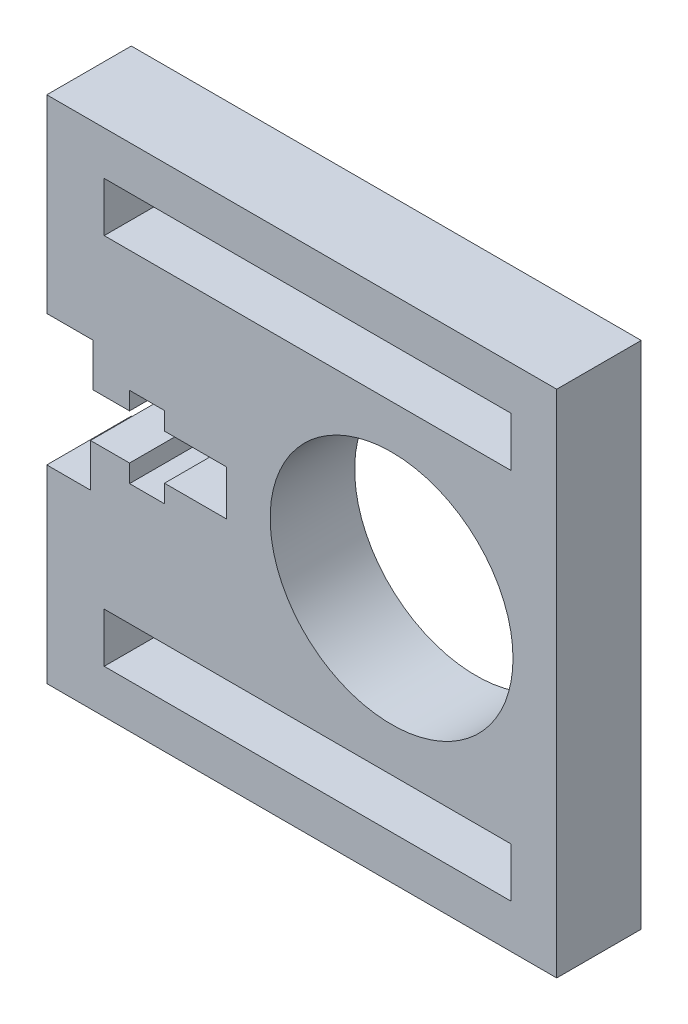
SolidWorks part; units mm, degrees
ref_plane "Front Plane" through (0, 0, 0) normal (0, 0, 1) x (1, 0, 0)
ref_plane "Top Plane" through (0, 0, 0) normal (0, 1, 0) x (1, 0, 0)
ref_plane "Right Plane" through (0, 0, 0) normal (1, 0, 0) x (0, 0, -1)
sketch "Sketch1" plane through (0, 0, 0) normal (0, 0, 1) x (1, 0, 0)
  line L0 (-17.7856, 22.0844) -> (-17.7856, 31.0844) construction
  line L1 (-5.455, 25.0366) -> (-5.455, 28.1323)
  line L3 (-17.7856, 22.0844) -> (-16.2856, 26.5844) construction
  line L5 (-11.9474, 23.8122) -> (-11.9474, 29.3567) construction
  line L6 (-16.2856, 26.5844) -> (-14.7856, 22.0844) construction
  line L7 (-9.7056, 23.8122) -> (-12.1056, 23.8122)
  line L8 (-17.7856, 22.0844) -> (-17.7856, 9.0844)
  line L9 (-12.1056, 25.0366) -> (-14.7856, 25.0366)
  line L10 (-14.7856, 25.0366) -> (-14.7856, 22.0844)
  line L11 (-12.1056, 25.0366) -> (-12.1056, 23.8122)
  line L12 (-17.7856, 9.0844) -> (17.2144, 9.0844)
  line L13 (-9.7056, 25.0366) -> (-9.7056, 23.8122)
  line L14 (-14.6056, 31.0844) -> (-17.7856, 31.0844) construction
  line L15 (-9.7056, 25.0366) -> (-5.455, 25.0366)
  line L16 (-16.2856, 26.5844) -> (-14.6056, 31.0844) construction
  line L17 (-17.7856, 31.0844) -> (-16.2856, 26.5844) construction
  line L19 (-14.7856, 22.0844) -> (-17.7856, 22.0844) construction
  line L20 (-14.6056, 31.0844) -> (-17.7856, 31.0844)
  line L21 (17.2144, 9.0844) -> (17.2144, 44.0844)
  line L22 (14.0846, 37.6844) -> (14.0846, 41.0856)
  line L23 (-13.8445, 15.4844) -> (14.0846, 15.4844)
  line L24 (-13.8445, 15.4844) -> (-13.8445, 12.0833)
  line L25 (-13.8445, 12.0833) -> (14.0846, 12.0833)
  line L26 (14.0846, 15.4844) -> (14.0846, 12.0833)
  line L27 (-14.7856, 22.0844) -> (-17.7856, 22.0844)
  line L28 (-13.8445, 41.0856) -> (14.0846, 41.0856)
  line L29 (-13.8445, 37.6844) -> (-13.8445, 41.0856)
  line L30 (-13.8445, 37.6844) -> (14.0846, 37.6844)
  line L31 (-9.7056, 28.1323) -> (-5.455, 28.1323)
  line L32 (-9.7056, 28.1323) -> (-9.7056, 29.3567)
  line L33 (-17.7856, 44.0844) -> (17.2144, 44.0844)
  line L34 (-12.1056, 28.1323) -> (-12.1056, 29.3567)
  line L35 (-14.6056, 28.1323) -> (-14.6056, 31.0844)
  line L36 (-12.1056, 28.1323) -> (-14.6056, 28.1323)
  line L37 (-17.7856, 31.0844) -> (-17.7856, 44.0844)
  line L38 (-9.7056, 29.3567) -> (-12.1056, 29.3567)
  line L39 (-5.455, 26.5844) -> (17.2144, 26.5844) construction
  ellipse E0 centre (5.8797, 26.5844) end of major axis (14.2144, 26.5844) minor radius 8.1
  point P18 (-16.2856, 26.5844)
  point P19 (-11.9474, 26.5844)
  point P25 (-17.7856, 26.5844)
  point P34 (17.2144, 26.5844)
  point P40 (-5.455, 26.5844)
  dimension "D6" = 5.5445
  dimension "D1" = 4.5
  dimension "D2" = 13
  dimension "D3" = 35
  dimension "D4" = 3
  dimension "D5" = 3
  dimension "D7" = 3.0957
  dimension "D8" = 2.4
  dimension "D9" = 2.5
  dimension "D10" = 3.18
extrude "Boss-Extrude1" add sketch "Sketch1" along normal blind 5.8
